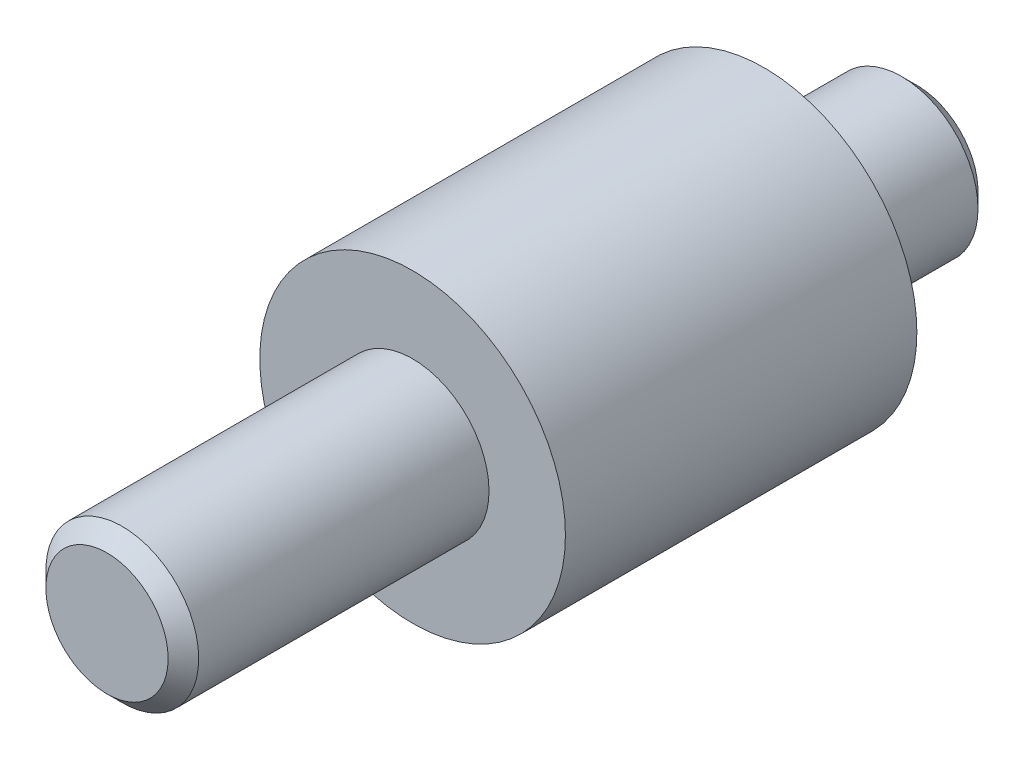
SolidWorks part; units mm, degrees
ref_plane "Front Plane" through (0, 0, 0) normal (0, 0, 1) x (1, 0, 0)
ref_plane "Top Plane" through (0, 0, 0) normal (0, 1, 0) x (1, 0, 0)
ref_plane "Right Plane" through (0, 0, 0) normal (1, 0, 0) x (0, 0, -1)
sketch "Sketch2" plane through (0, 0, 0) normal (0, 0, 1) x (1, 0, 0)
  circle A0 centre (0, 0) radius 10
  dimension "D1" = 20
extrude "Boss-Extrude1" add sketch "Sketch2" along normal blind 23
sketch "Sketch3" plane through (0, 0, 23) normal (0, 0, 1) x (1, 0, 0)
  circle A0 centre (0, 0) radius 5
  dimension "D1" = 10
extrude "Boss-Extrude2" add sketch "Sketch3" along normal blind 20 contours A0
sketch "Sketch4" plane through (0, 0, 0) normal (0, 0, -1) x (-1, 0, 0)
  circle A0 centre (0, 0) radius 5
  dimension "D1" = 10
extrude "Boss-Extrude3" add sketch "Sketch4" along normal blind 10
chamfer "Chamfer1" distance 1 angle 45 1 edges at (-5, 0, -10)
chamfer "Chamfer2" distance 1 angle 45 1 edges at (5, 0, 43)
